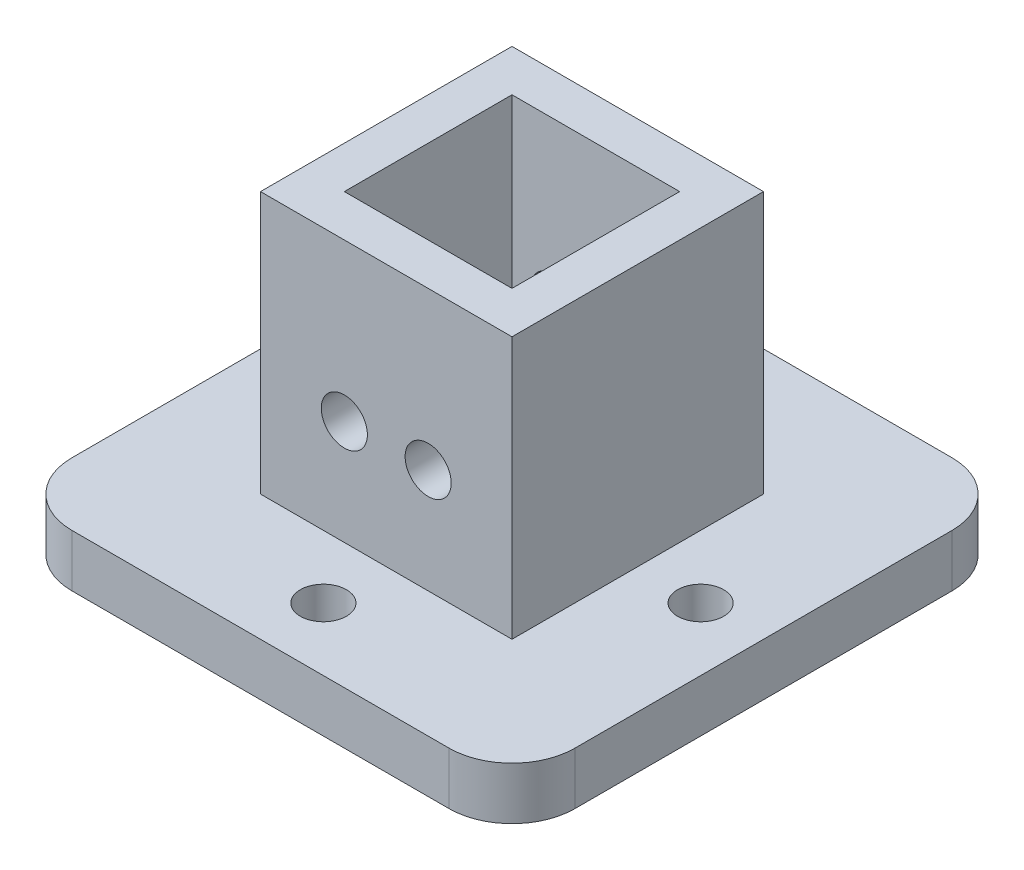
SolidWorks part; units mm, degrees
ref_plane "前视基准面" through (0, 0, 0) normal (0, 0, 1) x (1, 0, 0)
ref_plane "上视基准面" through (0, 0, 0) normal (0, 1, 0) x (1, 0, 0)
ref_plane "右视基准面" through (0, 0, 0) normal (1, 0, 0) x (0, 0, -1)
sketch "草图1" plane through (0, 0, 0) normal (0, 1, 0) x (1, 0, 0)
  line L0 (0, 0) -> (0, 24)
  line L1 (0, 0) -> (24, 0)
  line L2 (0, 24) -> (24, 24)
  line L3 (24, 0) -> (24, 24)
  line L4 (0, 0) -> (0, 20)
  line L5 (0, 0) -> (20, 0)
  line L6 (4, 20) -> (20, 20)
  line L7 (20, 4) -> (20, 20)
  line L8 (20, 20) -> (4, 20)
  line L9 (20, 20) -> (20, 4)
  line L10 (4, 20) -> (4, 4)
  line L11 (20, 4) -> (4, 4)
extrude "凸台-拉伸1" add sketch "草图1" along normal blind 30 contours L1 L3 L2 L0 L7 L11 L10 L6
sketch "草图2" plane through (0, 0, 0) normal (0, 0, 1) x (1, 0, 0)
  circle A0 centre (8, 15) radius 2.2
  circle A1 centre (16, 15) radius 2.2
extrude "切除-拉伸1" cut sketch "草图2" against normal blind 31
sketch "草图3" plane through (0, 0, 0) normal (0, -1, 0) x (1, 0, 0)
  line L5 (-6, -30) -> (-12, -30)
  line L6 (0, -24) -> (24, 0)
  line L7 (0, 0) -> (24, 0)
  line L8 (0, 6) -> (-6, 6)
  line L9 (-6, 6) -> (-6, -30)
  line L10 (-6, -30) -> (30, -30)
  line L11 (30, -30) -> (30, 6)
  line L12 (30, 6) -> (0, 6)
  line L13 (0, 0) -> (0, -24)
  line L14 (24, 0) -> (24, -24)
  line L15 (0, -24) -> (24, -24)
  line L16 (-6, -30) -> (-6, -36)
  line L17 (-12, -30) -> (-12, -36)
  line L18 (-6, -36) -> (-12, -36)
  line L19 (30, 6) -> (30, 12)
  line L20 (30, 6) -> (36, 6)
  line L21 (30, 12) -> (36, 12)
  line L22 (36, 6) -> (36, 12)
  line L23 (-12, -36) -> (-12, 12)
  line L24 (-12, -36) -> (36, -36)
  line L25 (-12, 12) -> (36, 12)
  line L26 (36, -36) -> (36, 12)
  line M1 (24, 0) -> (0, 0)
  line M2 (0, 0) -> (0, -24)
  line M3 (0, -24) -> (24, -24)
  line M4 (24, -24) -> (24, 0)
extrude "凸台-拉伸3" add sketch "草图3" against normal blind 5 contours L18 L16 L5 L17 | L25 L23 L5 L9 L8 L12 L19 | L11 L12 L8 L9 L10 M1 M4 M3 M2 | L24 L26 L20 L11 L10 L16 | L20 L22 L21 L19
fillet "圆角1" radius 6 4 edges at (-12, 2.5, 12) (36, 2.5, 12) (-12, 2.5, -36) (36, 2.5, -36)
sketch "草图4" plane through (0, 5, 0) normal (0, 1, 0) x (1, 0, 0)
  circle A0 centre (12, -6) radius 2.2
  circle A1 centre (-6, 12) radius 2.2
  circle A2 centre (12, 30) radius 2.2
  circle A3 centre (30, 12) radius 2.2
  point P9 (12, 12)
  point P15 (12, 12)
  dimension "D1" = 4
extrude "切除-拉伸2" cut sketch "草图4" against normal blind 5
